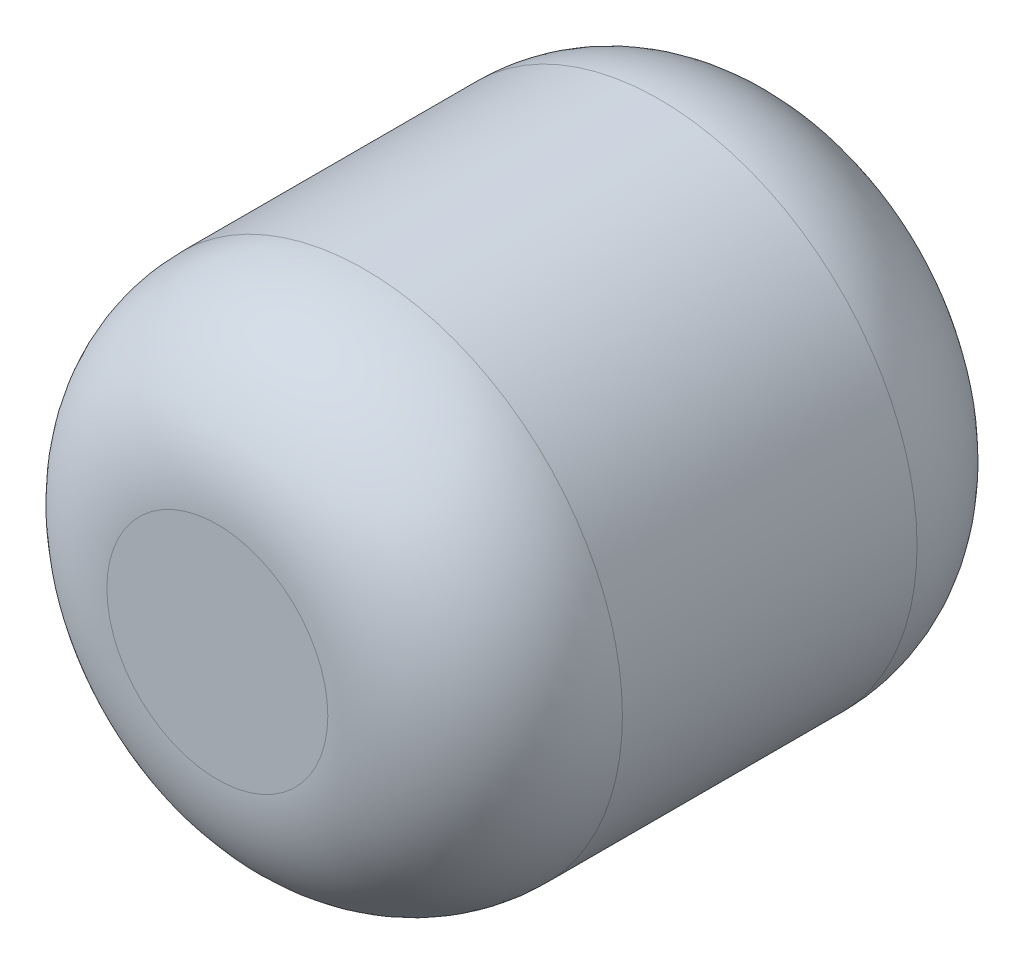
SolidWorks part; units mm, degrees
ref_plane "Plan de face" through (0, 0, 0) normal (0, 0, 1) x (1, 0, 0)
ref_plane "Plan de dessus" through (0, 0, 0) normal (0, 1, 0) x (1, 0, 0)
ref_plane "Plan de droite" through (0, 0, 0) normal (1, 0, 0) x (0, 0, -1)
sketch "Esquisse1" plane through (0, 0, 0) normal (0, 0, 1) x (1, 0, 0)
  circle A0 centre (0, 0) radius 44.45
  dimension "D1" = 88.9
extrude "Boss.-Extru.1" add sketch "Esquisse1" along normal blind 101.6
fillet "Congé1" radius 25.4 2 edges at (44.45, 0, 0) (44.45, 0, 101.6)
